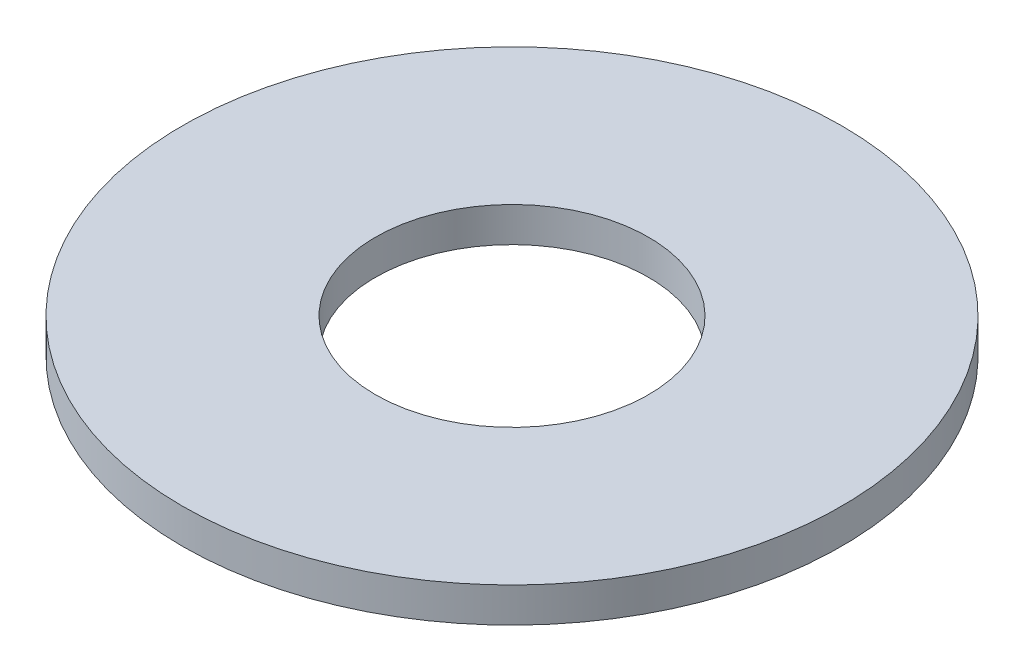
SolidWorks part; units mm, degrees
ref_plane "Front Plane" through (0, 0, 0) normal (0, 0, 1) x (1, 0, 0)
ref_plane "Top Plane" through (0, 0, 0) normal (0, 1, 0) x (1, 0, 0)
ref_plane "Right Plane" through (0, 0, 0) normal (1, 0, 0) x (0, 0, -1)
sketch "Sketch1" plane through (0, 0, 0) normal (0, 1, 0) x (1, 0, 0)
  circle A0 centre (0, 0) radius 37.9
  circle A1 centre (0, 0) radius 15.7
  dimension "D1" = 31.4
  dimension "D2" = 75.8
extrude "Boss-Extrude1" add sketch "Sketch1" along normal blind 4
